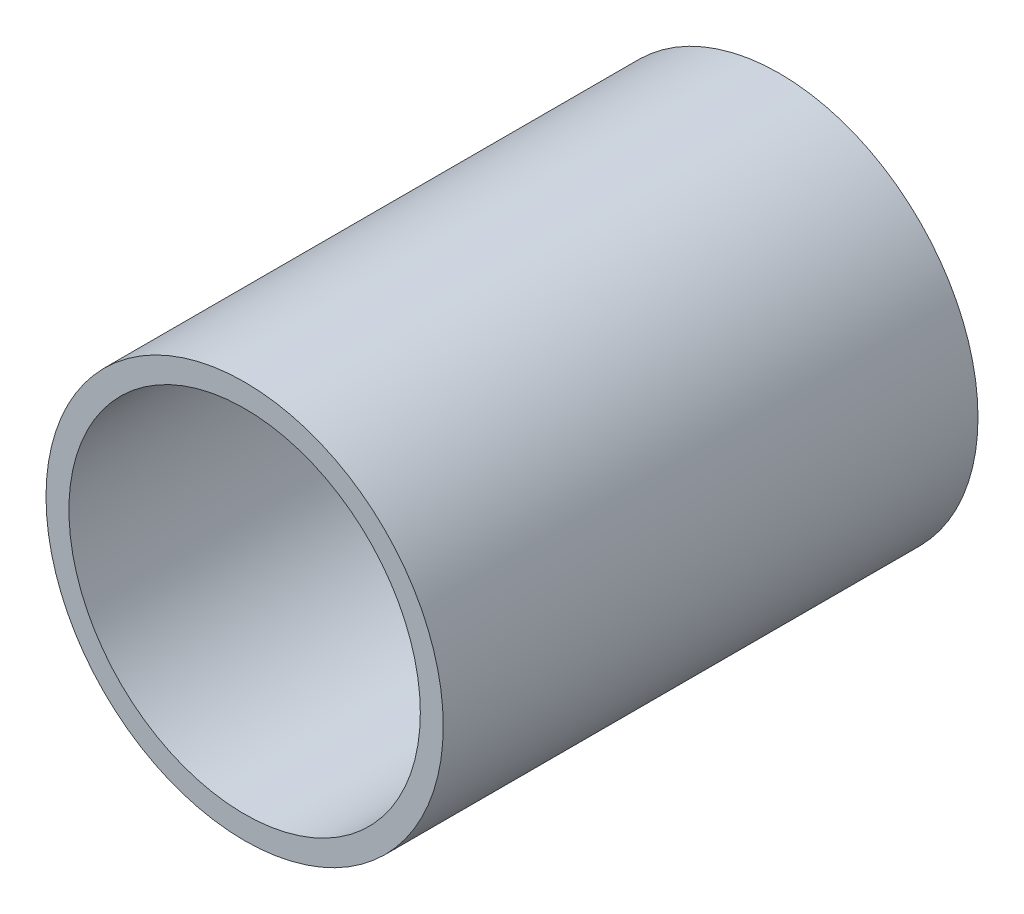
SolidWorks part; units mm, degrees
ref_plane "Front Plane" through (0, 0, 0) normal (0, 0, 1) x (1, 0, 0)
ref_plane "Top Plane" through (0, 0, 0) normal (0, 1, 0) x (1, 0, 0)
ref_plane "Right Plane" through (0, 0, 0) normal (1, 0, 0) x (0, 0, -1)
sketch "Sketch1" plane through (0, 0, 0) normal (0, 0, 1) x (1, 0, 0)
  circle A0 centre (0, 0) radius 26
  dimension "D1" = 52
extrude "Boss-Extrude1" add sketch "Sketch1" along normal blind 70
sketch "Sketch2" plane through (0, 0, 70) normal (0, 0, 1) x (1, 0, 0)
  circle A0 centre (0, 0) radius 23
  dimension "D1" = 46
extrude "Cut-Extrude1" cut sketch "Sketch2" against normal up to next
